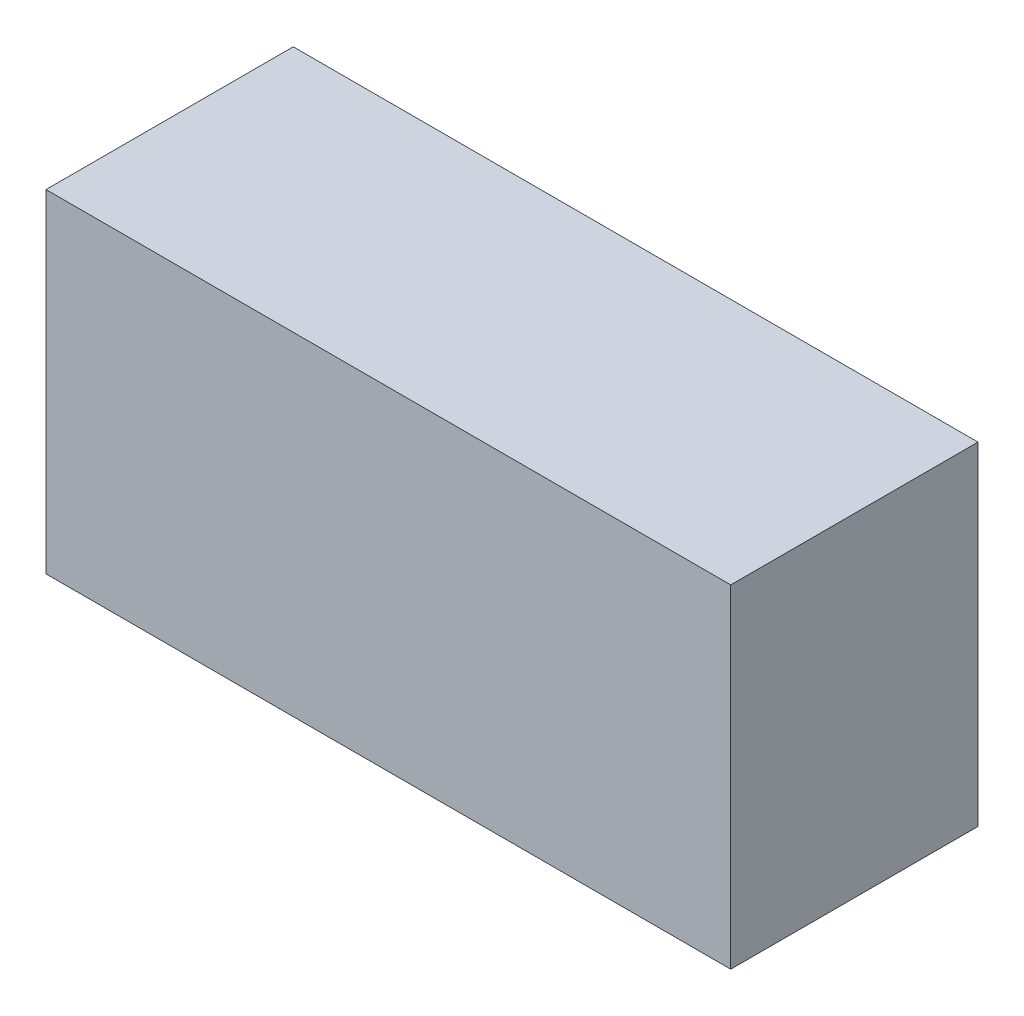
SolidWorks part; units mm, degrees
ref_plane "Front Plane" through (0, 0, 0) normal (0, 0, 1) x (1, 0, 0)
ref_plane "Top Plane" through (0, 0, 0) normal (0, 1, 0) x (1, 0, 0)
ref_plane "Right Plane" through (0, 0, 0) normal (1, 0, 0) x (0, 0, -1)
sketch "Sketch1" plane through (0, 0, 0) normal (0, 1, 0) x (1, 0, 0)
  line L1 (-36, 13) -> (36, 13)
  line L2 (-36, 13) -> (-36, -13)
  line L3 (-36, -13) -> (36, -13)
  line L4 (36, 13) -> (36, -13)
  line L5 (-36, 13) -> (36, -13) construction
  line L6 (-36, -13) -> (36, 13) construction
  point P0 (0, 0)
  dimension "D1" = 26
  dimension "D2" = 72
extrude "Boss-Extrude1" add sketch "Sketch1" along normal blind 35
sketch "Sketch2" plane through (0, 22.5, -13) normal (0, 0, 1) x (1, 0, 0)
  line L0 (-28.3988, -3.7327) -> (28.3988, -3.7327) construction
  text T0 "Bateria 11.1v\r\n" font "Century Gothic" height 5
  point P2 (0, -3.7327)
extrude "Boss-Extrude2" add sketch "Sketch2" against normal blind 1
